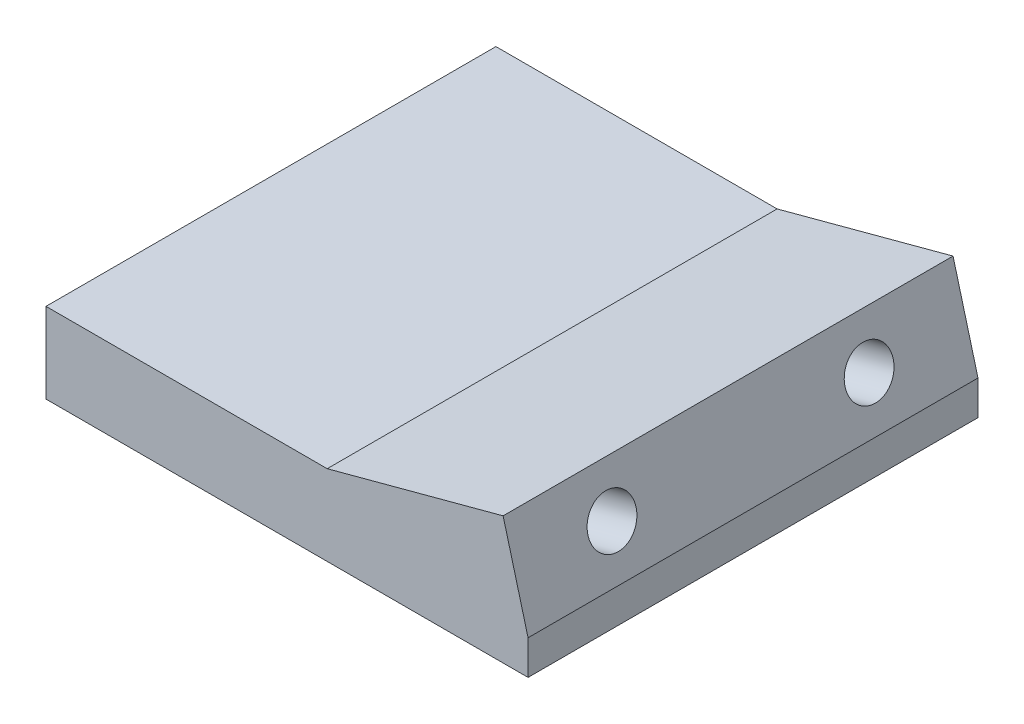
SolidWorks part; units mm, degrees
material "ABS"
ref_plane "Front Plane" through (0, 0, 0) normal (0, 0, 1) x (1, 0, 0)
ref_plane "Top Plane" through (0, 0, 0) normal (0, 1, 0) x (1, 0, 0)
ref_plane "Right Plane" through (0, 0, 0) normal (1, 0, 0) x (0, 0, -1)
sketch "Sketch1" plane through (0, 0, 0) normal (0, 0, 1) x (1, 0, 0)
  line L0 (95.25, 0) -> (95.25, 6.7872)
  line L1 (0, 0) -> (95.25, 0)
  line L2 (0, 0) -> (0, 15.875)
  line L3 (0, 15.875) -> (55.5625, 15.875)
  line L5 (95.25, 6.7872) -> (90.3195, 25.1881)
  line L6 (55.5625, 15.875) -> (90.3195, 25.1881)
  line L7 (92.7847, 15.9877) -> (33.118, 0) construction
  point P5 (37.4681, 0)
  point P10 (36.0335, 0)
  dimension "D1" = 15
  dimension "D2" = 95.25
  dimension "D3" = 19.05
  dimension "D4" = 15.875
  dimension "D5" = 55.5625
extrude "Boss-Extrude1" add sketch "Sketch1" along normal mid plane 88.9
hole_wizard "3/8 (0.375) Diameter Hole1" positions "Sketch2" profile "Sketch3" hole size "3/8" standard "ANSI Inch" end condition through all
sketch "Sketch2" plane through (90.5663, 24.2672, 0) normal (0.9659, 0.2588, 0) x (0, 0, -1)
  line L0 (0, -18.0966) -> (0, 0.9534) construction
  line L1 (-44.45, -18.0966) -> (44.45, -18.0966) construction
  line L2 (-44.45, 0.9534) -> (44.45, 0.9534) construction
  line L4 (-25.4, 0.9534) -> (-25.4, -18.0966) construction
  point P0 (-25.4, -8.5716)
  point P2 (25.4, -8.5716)
  point P26 (-15.5483, -40.8776)
  dimension "D1" = 50.8
sketch "Sketch3" plane through (92.7847, 15.9877, 25.4) normal (0, 0, 1) x (-0.2588, 0.9659, 0)
  line L0 (0, 0) -> (0, 93.7611)
  line L1 (0, 93.7611) -> (4.7625, 93.7611)
  line L2 (4.7625, 93.7611) -> (4.7625, 0)
  line L5 (4.7625, 0) -> (0, 0)
  line L11 (0, -6.35) -> (0, 107.95) construction
  dimension "Thru Hole Dia." = 9.525
  dimension "Thru Hole Depth" = 93.7611
